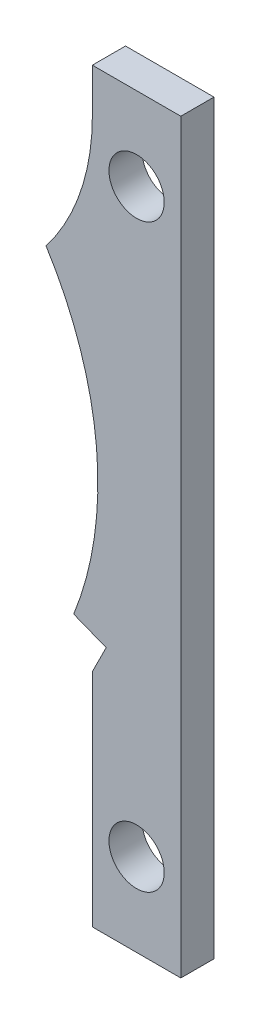
SolidWorks part; units mm, degrees
ref_plane "Front Plane" through (0, 0, 0) normal (0, 0, 1) x (1, 0, 0)
ref_plane "Top Plane" through (0, 0, 0) normal (0, 1, 0) x (1, 0, 0)
ref_plane "Right Plane" through (0, 0, 0) normal (1, 0, 0) x (0, 0, -1)
sketch "Sketch1" plane through (0, 0, 0) normal (0, 0, 1) x (1, 0, 0)
  line L0 (76, 62) -> (60, 62) construction
  line L1 (60, 62) -> (60, 57)
  line L3 (62.5, -25) -> (60, -30)
  line L4 (60, -30) -> (60, -70)
  line L5 (60, -70) -> (76, -70)
  line L6 (76, -70) -> (76, 62)
  line L7 (60, -70) -> (0, -70) construction
  line L8 (0, -70) -> (0, 0) construction
  line L9 (62.5, -25) -> (60, -24.0119)
  line L12 (60, 57) -> (20, 57) construction
  line L13 (60, -24.0119) -> (56.6274, -22.679)
  line L14 (60, 62) -> (60, 65)
  line L15 (60, 65) -> (76, 65)
  line L16 (76, 65) -> (76, 62)
  circle A3 centre (0, 0) radius 60 construction
  arc A6 (51.6201, 32.5017) -> (60, 57) centre (20, 57) ccw
  arc A10 (56.6274, -22.679) -> (51.6201, 32.5017) centre (0, 0) ccw
  dimension "D4" = 120
  dimension "D5" = 85
  dimension "D8" = 1
  dimension "D9" = 3
  dimension "D1" = 132
  dimension "D2" = 16
  dimension "D3" = 16
  dimension "D6" = 2.5
  dimension "D7" = 40
  dimension "D10" = 5
  dimension "D11" = 5
  dimension "D12" = 40
  dimension "D15" = 60
  dimension "D16" = 70
extrude "Boss-Extrude1" add sketch "Sketch1" along normal mid plane 6
sketch "Sketch3" plane through (0, 0, 0) normal (0, 0, 1) x (1, 0, 0)
  line L0 (68, 52.3928) -> (68, 80.2645) construction
  line L4 (76, -70) -> (68, -70) construction
  line L5 (60, -70) -> (76, -70) construction
  line L6 (68, -70) -> (68, -58) construction
  dimension "D2" = 12
hole_wizard "Ø10.0 (10) Diameter Hole1" positions "3DSketch1" profile "Sketch8" hole size "Ø10.0" standard "AS" end condition through all
sketch3d "3DSketch1"
  line L0 (76, 65, 3) -> (60, 65, 3) construction
  line L1 (76, -70, 3) -> (76, 65, 3) construction
  line L2 (60, -70, 3) -> (76, -70, 3) construction
  point P0 (68, 50, 3)
  point P7 (68, -55, 3)
  dimension "D1" = 15
  dimension "D2" = 8
  dimension "D3" = 8
  dimension "D4" = 15
sketch "Sketch8" plane through (68, 50, 3) normal (1, 0, 0) x (0, -1, 0)
  line L0 (0, 0) -> (0, 6)
  line L1 (0, 6) -> (5, 6)
  line L2 (5, 6) -> (5, 0)
  line L5 (5, 0) -> (0, 0)
  line L11 (0, -6.35) -> (0, 107.95) construction
  dimension "Thru Hole Dia." = 10
  dimension "Thru Hole Depth" = 6
